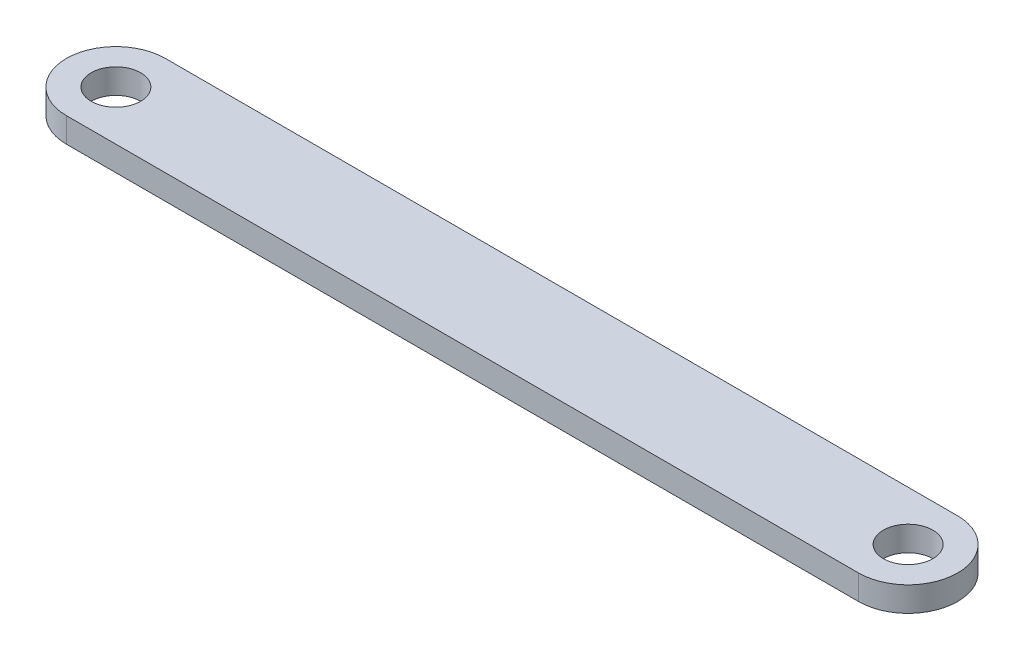
SolidWorks part; units mm, degrees
ref_plane "Ön Düzlem" through (0, 0, 0) normal (0, 0, 1) x (1, 0, 0)
ref_plane "Üst Düzlem" through (0, 0, 0) normal (0, 1, 0) x (1, 0, 0)
ref_plane "Sağ Düzlem" through (0, 0, 0) normal (1, 0, 0) x (0, 0, -1)
sketch "Sketch1" plane through (0, 0, 0) normal (0, 1, 0) x (1, 0, 0)
  line L0 (-80, 0) -> (80, 0) construction
  line L1 (-80, 10) -> (80, 10)
  line L2 (-80, -10) -> (80, -10)
  arc A0 (-80, 10) -> (-80, -10) centre (-80, 0) ccw
  arc A1 (80, -10) -> (80, 10) centre (80, 0) ccw
  circle A2 centre (-80, 0) radius 5
  circle A3 centre (80, 0) radius 5
  point P2 (0, 0)
  dimension "D1" = 10
  dimension "D3" = 10
  dimension "D4" = 10
  dimension "D2" = 160
extrude "Boss-Extrude1" add sketch "Sketch1" along normal blind 5
